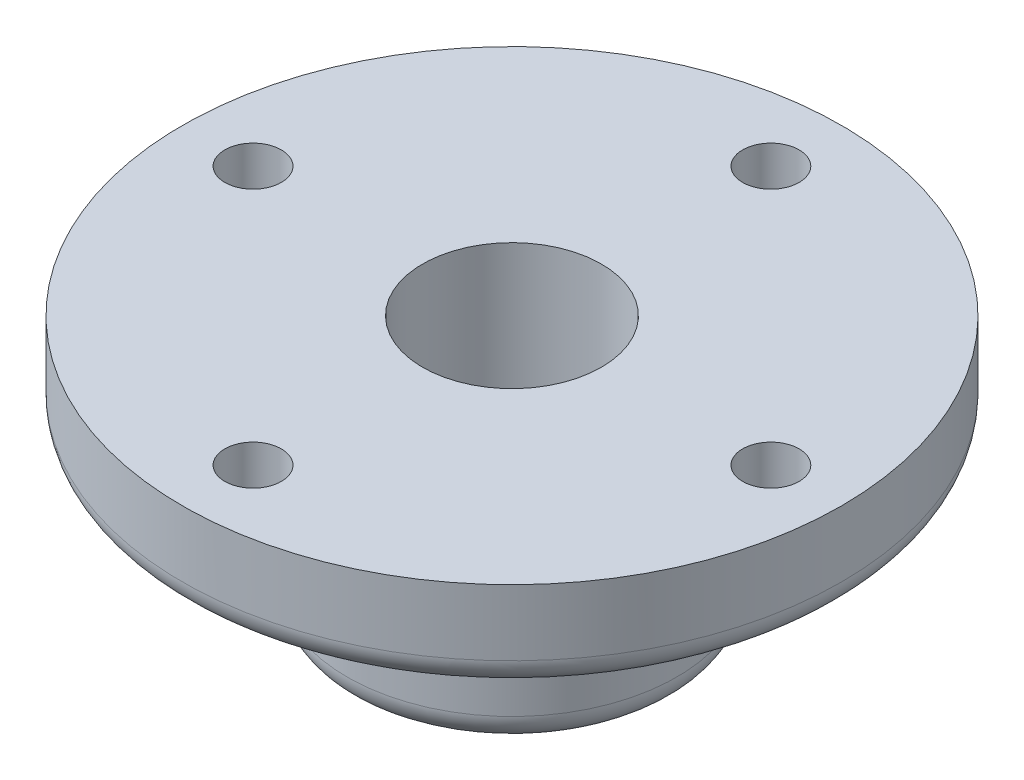
SolidWorks part; units mm, degrees
ref_plane "Front Plane" through (0, 0, 0) normal (0, 0, 1) x (1, 0, 0)
ref_plane "Top Plane" through (0, 0, 0) normal (0, 1, 0) x (1, 0, 0)
ref_plane "Right Plane" through (0, 0, 0) normal (1, 0, 0) x (0, 0, -1)
sketch "Sketch1" plane through (0, 0, 0) normal (0, 0, 1) x (1, 0, 0)
  line L8 (0, -1000) -> (0, 49000) construction
  line L9 (-19, 0) -> (-70, 0)
  line L10 (-70, 0) -> (-70, -20)
  line L11 (-70, -20) -> (-35, -20)
  line L12 (-35, -20) -> (-35, -55)
  line L13 (-35, -55) -> (-19, -55)
  line L14 (-19, -55) -> (-19, 0)
  dimension "D1" = 140
  dimension "D2" = 38
  dimension "D3" = 70
  dimension "D4" = 55
  dimension "D5" = 20
revolve "Revolve2" add sketch "Sketch1" angle 360 about L8
fillet "Fillet1" radius 6 3 edges at (35, -20, 0) (35, -55, 0) (70, -20, 0)
sketch "Sketch2" plane through (0, 0, 0) normal (0, 1, 0) x (1, 0, 0)
  circle A0 centre (0, 55) radius 6
  circle A1 centre (55, 0) radius 6
  circle A2 centre (0, -55) radius 6
  circle A3 centre (-55, 0) radius 6
  point P13 (0, 0)
  dimension "D1" = 12
  dimension "D2" = 55
  dimension "D3" = 4
extrude "Cut-Extrude1" cut sketch "Sketch2" against normal through all
